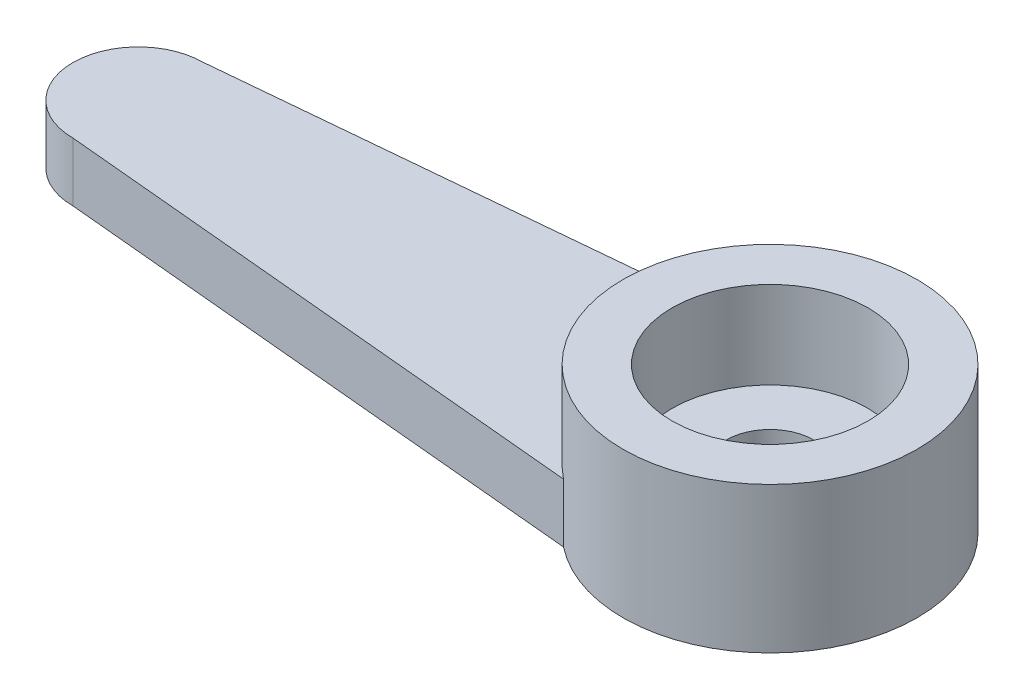
SolidWorks part; units mm, degrees
ref_plane "Piano frontale" through (0, 0, 0) normal (0, 0, 1) x (1, 0, 0)
ref_plane "Piano superiore" through (0, 0, 0) normal (0, 1, 0) x (1, 0, 0)
ref_plane "Piano destro" through (0, 0, 0) normal (1, 0, 0) x (0, 0, -1)
sketch "Schizzo1" plane through (0, 0, 0) normal (0, 1, 0) x (1, 0, 0)
  line L0 (-2.09, 2.65) -> (-14.5, 1.5)
  line L1 (-2.09, -2.65) -> (-14.5, -1.5)
  line L2 (-2.09, 2.65) -> (-2.09, -2.65)
  circle A0 centre (0, 0) radius 3.375
  arc A1 (-14.5, 1.5) -> (-14.5, -1.5) centre (-14.5, 0) ccw
  point P8 (-2.09, 0)
  point P13 (-16, 0)
  dimension "D1" = 6.75
  dimension "D3" = 1.5
  dimension "D2" = 5.3
  dimension "D4" = 3
  dimension "D5" = 16
extrude "Estrusione-Estrusione1" add sketch "Schizzo1" along normal blind 1.35 contours L0 A1 L1 A0 | L2 A0 | L2 A0
sketch "Schizzo2" plane through (0, 1.35, 0) normal (0, 1, 0) x (1, 0, 0)
  circle A0 centre (0, 0) radius 3.375
extrude "Estrusione-Estrusione2" add sketch "Schizzo2" along normal blind 2
sketch "Schizzo3" plane through (0, 3.35, 0) normal (0, 1, 0) x (1, 0, 0)
  circle A0 centre (0, 0) radius 2.25
  dimension "D1" = 4.5
extrude "Taglio-Estrusione1" cut sketch "Schizzo3" against normal blind 2
sketch "Schizzo4" plane through (0, 1.35, 0) normal (0, 1, 0) x (1, 0, 0)
  circle A0 centre (0, 0) radius 1
  dimension "D1" = 2
extrude "Taglio-Estrusione2" cut sketch "Schizzo4" against normal through all
